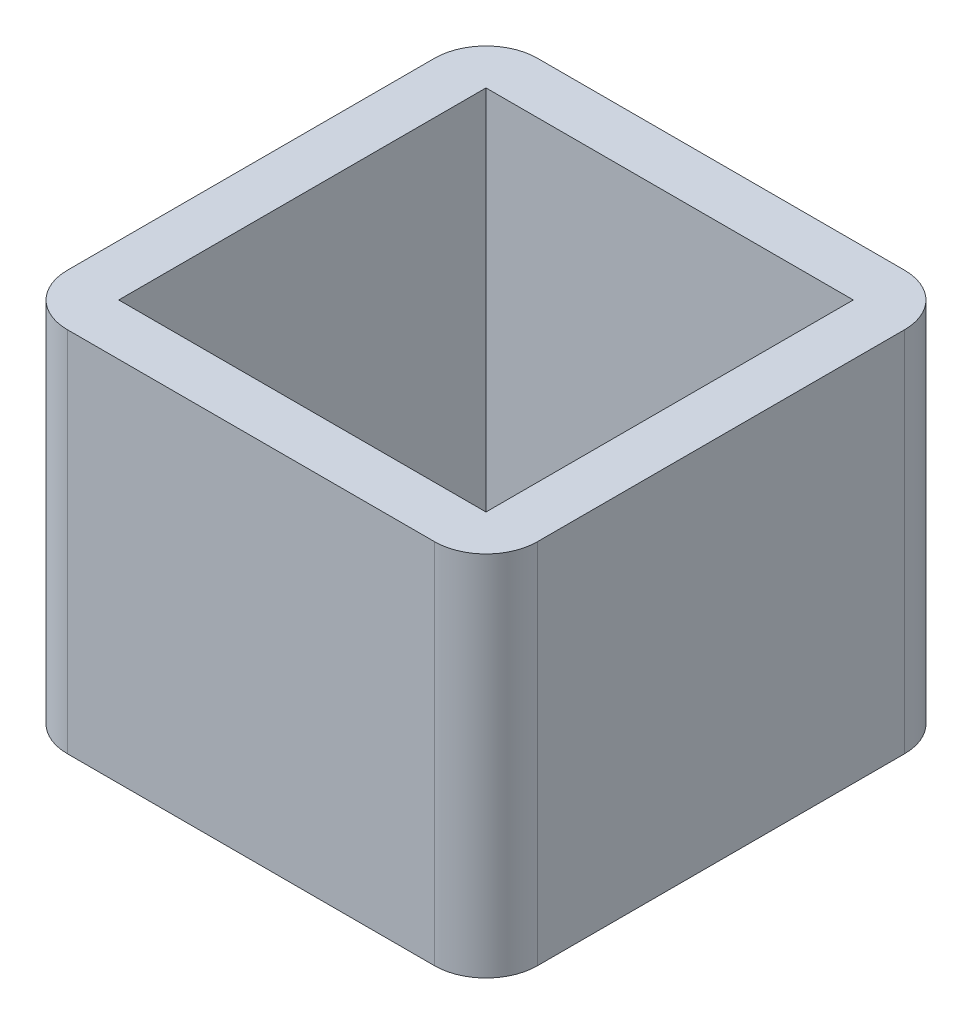
SolidWorks part; units mm, degrees
ref_plane "Front Plane" through (0, 0, 0) normal (0, 0, 1) x (1, 0, 0)
ref_plane "Top Plane" through (0, 0, 0) normal (0, 1, 0) x (1, 0, 0)
ref_plane "Right Plane" through (0, 0, 0) normal (1, 0, 0) x (0, 0, -1)
sketch "Sketch1" plane through (0, 0, 0) normal (0, 1, 0) x (1, 0, 0)
  line L1 (2.8, 0) -> (22.8, 0)
  line L2 (0, -2.8) -> (0, -22.8)
  line L3 (2.8, -25.6) -> (22.8, -25.6)
  line L4 (25.6, -2.8) -> (25.6, -22.8)
  arc A0 (22.8, 0) -> (25.6, -2.8) centre (22.8, -2.8) cw
  arc A1 (22.8, -25.6) -> (25.6, -22.8) centre (22.8, -22.8) ccw
  arc A2 (0, -22.8) -> (2.8, -25.6) centre (2.8, -22.8) ccw
  arc A3 (2.8, 0) -> (0, -2.8) centre (2.8, -2.8) ccw
  point P7 (25.6, 0)
  point P10 (25.6, -25.6)
  point P15 (0, 0)
  dimension "D2" = 2.8
  dimension "D1" = 25.6
extrude "Boss-Extrude1" add sketch "Sketch1" along normal blind 20
sketch "Sketch3" plane through (0, 0, 0) normal (0, -1, 0) x (-1, 0, 0)
  line L4 (-2.8, -2.8) -> (-22.8, -2.8)
  line L5 (-2.8, -2.8) -> (-2.8, -22.8)
  line L6 (-2.8, -22.8) -> (-22.8, -22.8)
  line L7 (-22.8, -2.8) -> (-22.8, -22.8)
  line L8 (-2.8, -2.8) -> (-22.8, -22.8) construction
  line L9 (-2.8, -22.8) -> (-22.8, -2.8) construction
  point P6 (-12.8, -12.8)
extrude "Cut-Extrude1" cut sketch "Sketch3" against normal blind 1040.5
